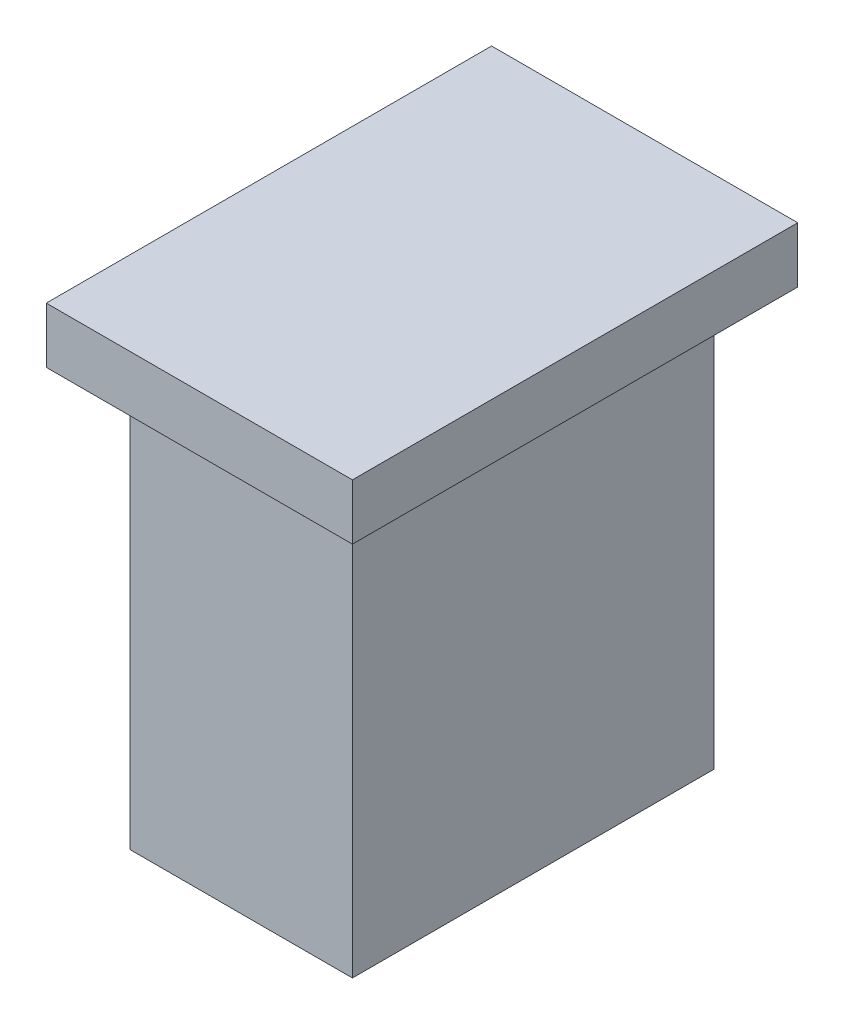
SolidWorks part; units mm, degrees
ref_plane "Спереди" through (0, 0, 0) normal (0, 0, 1) x (1, 0, 0)
ref_plane "Сверху" through (0, 0, 0) normal (0, 1, 0) x (1, 0, 0)
ref_plane "Справа" through (0, 0, 0) normal (1, 0, 0) x (0, 0, -1)
sketch "Эскиз1" plane through (0, 0, 0) normal (0, 1, 0) x (1, 0, 0)
  line L1 (-4, 6.5) -> (4, 6.5)
  line L2 (-4, 6.5) -> (-4, -6.5)
  line L3 (-4, -6.5) -> (4, -6.5)
  line L4 (4, 6.5) -> (4, -6.5)
  line L5 (-4, 6.5) -> (4, -6.5) construction
  line L6 (-4, -6.5) -> (4, 6.5) construction
  point P0 (0, 0)
  dimension "D1" = 8
  dimension "D2" = 13
extrude "Бобышка-Вытянуть1" add sketch "Эскиз1" along normal blind 15
sketch "Эскиз2" plane through (0, 15, 0) normal (0, 1, 0) x (1, 0, 0)
  line L1 (-5.5, 8) -> (5.5, 8)
  line L2 (-5.5, 8) -> (-5.5, -8)
  line L3 (-5.5, -8) -> (5.5, -8)
  line L4 (5.5, 8) -> (5.5, -8)
  line L5 (-5.5, 8) -> (5.5, -8) construction
  line L6 (-5.5, -8) -> (5.5, 8) construction
  point P0 (0, 0)
  dimension "D1" = 11
  dimension "D2" = 16
extrude "Бобышка-Вытянуть2" add sketch "Эскиз2" along normal blind 2
